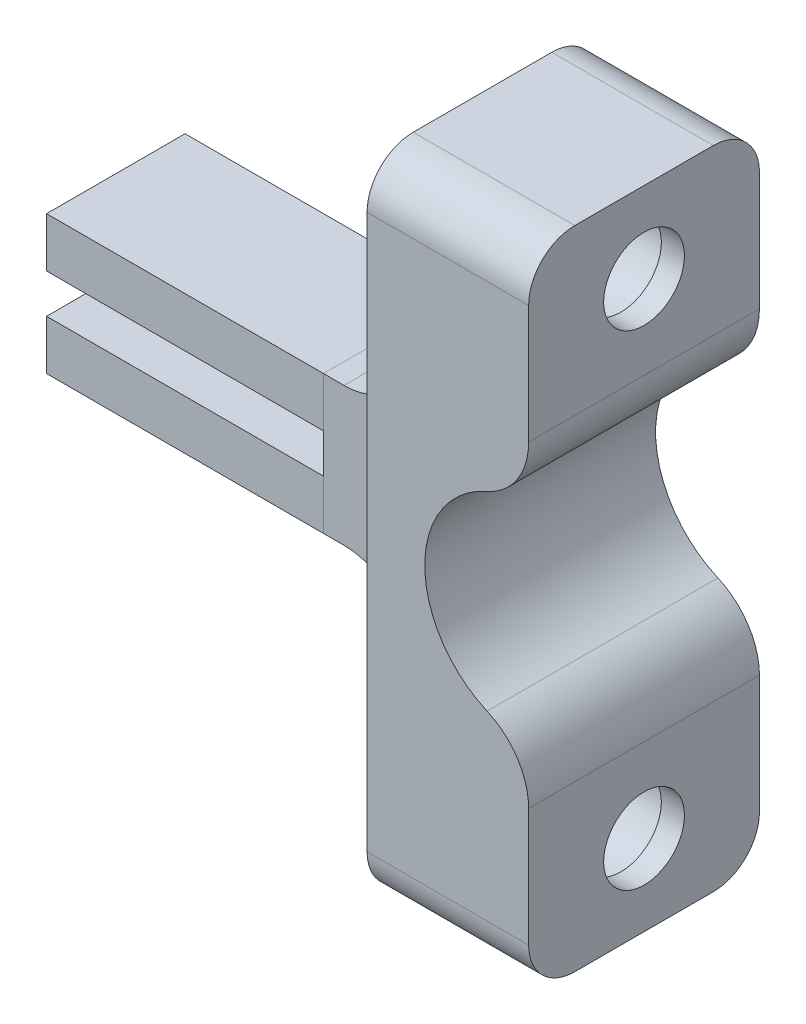
SolidWorks part; units mm, degrees
ref_plane "Front Plane" through (0, 0, 0) normal (0, 0, 1) x (1, 0, 0)
ref_plane "Top Plane" through (0, 0, 0) normal (0, 1, 0) x (1, 0, 0)
ref_plane "Right Plane" through (0, 0, 0) normal (1, 0, 0) x (0, 0, -1)
sketch "Sketch1" plane through (0, 0, 0) normal (0, 0, 1) x (1, 0, 0)
  line L1 (-6, -3) -> (6, -3)
  line L2 (-6, -3) -> (-6, 3)
  line L3 (-6, 3) -> (6, 3)
  line L4 (6, -3) -> (6, 3)
  line L5 (-6, -3) -> (6, 3) construction
  line L6 (-6, 3) -> (6, -3) construction
  line L7 (-6, -0.85) -> (6, -0.85)
  line L8 (-6, -0.85) -> (-6, 0.85)
  line L9 (-6, 0.85) -> (6, 0.85)
  line L10 (6, -0.85) -> (6, 0.85)
  line L11 (-6, -0.85) -> (6, 0.85) construction
  line L12 (-6, 0.85) -> (6, -0.85) construction
  point P0 (0, 0)
  point P6 (0, 0)
  dimension "D1" = 1.7
  dimension "D2" = 12
  dimension "D3" = 6
extrude "Boss-Extrude1" add sketch "Sketch1" along normal mid plane 6 contours L2 L9 L4 L3 | L7 L2 L1 L4
sketch "Sketch2" plane through (0, 0, 3) normal (0, 0, 1) x (1, 0, 0)
  line L1 (6, 3) -> (10, 3)
  line L2 (6, 3) -> (6, -3)
  line L3 (6, -3) -> (10, -3)
  line L4 (10, 3) -> (10, -3)
  dimension "D1" = 6
  dimension "D2" = 4
extrude "Boss-Extrude2" add sketch "Sketch2" against normal blind 6 separate body
sketch "Sketch3" plane through (0, 0, 0) normal (0, 0, 1) x (1, 0, 0)
  line L1 (9.8883, 14) -> (16.8883, 14)
  line L2 (9.8883, 14) -> (9.8883, -14)
  line L3 (9.8883, -14) -> (16.8883, -14)
  line L4 (16.8883, 14) -> (16.8883, -14)
  point P4 (9.8883, 0)
  dimension "D1" = 28
  dimension "D2" = 7
extrude "Boss-Extrude3" add sketch "Sketch3" along normal mid plane 10
sketch "Sketch5" plane through (0, 0, 5) normal (0, 0, 1) x (1, 0, 0)
  line L0 (16.8883, -14) -> (16.8883, 14) construction
  circle A0 centre (16.8883, 0) radius 4.5
  dimension "D1" = 9
extrude "Cut-Extrude1" cut sketch "Sketch5" against normal through all both and the other way through all
fillet "Fillet1" radius 3 4 edges at (16.8883, 4.5, 0) (16.8883, -4.5, 0) (9.8883, -3, 0) (9.8883, 3, 0)
fillet "Fillet2" radius 2 4 edges at (13.3883, 14, -5) (13.3883, -14, -5) (13.3883, -14, 5) (13.3883, 14, 5)
sketch "Sketch6" plane through (16.8883, 0, 0) normal (1, 0, 0) x (0, 0, -1)
  line L0 (-3, 14) -> (3, 14) construction
  line L1 (-3, -14) -> (3, -14) construction
  circle A0 centre (0, 10.5) radius 2.25
  circle A1 centre (0, -10.5) radius 2.25
  dimension "D1" = 4.5
  dimension "D2" = 4.5
  dimension "D4" = 3.5
  dimension "D3" = 3.5
extrude "Cut-Extrude2" cut sketch "Sketch6" against normal blind 16
sketch "Sketch7" plane through (16.8883, 0, 0) normal (1, 0, 0) x (0, 0, -1)
  circle A0 centre (0, 10.5) radius 1.75
  circle A1 centre (0, -10.5) radius 1.75
  circle A2 centre (0, 10.5) radius 3.027
  circle A3 centre (0, -10.5) radius 2.865
  dimension "D1" = 3.5
  dimension "3.5" = 3.5
extrude "Boss-Extrude4" add sketch "Sketch7" against normal blind 1
